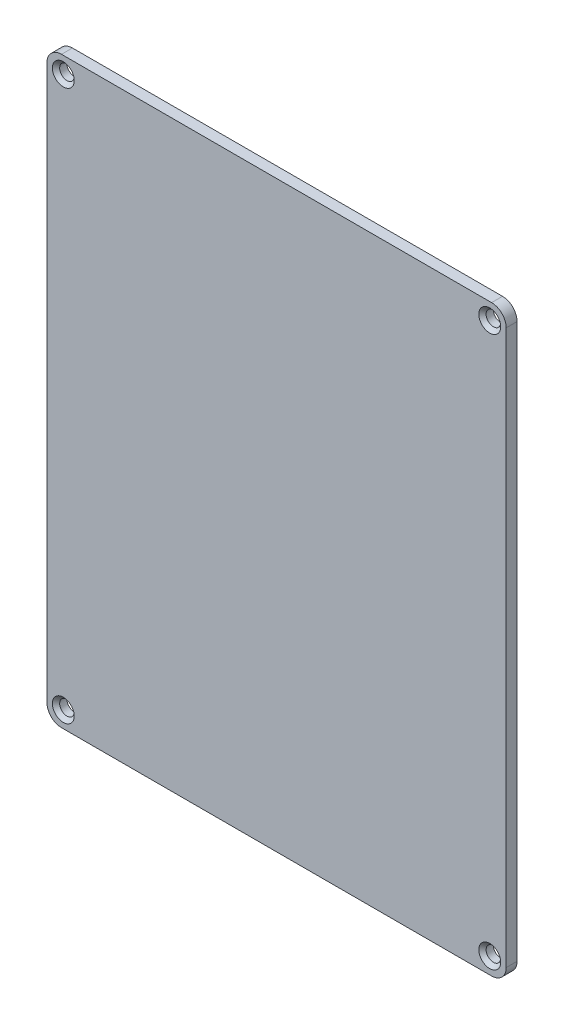
SolidWorks part; units mm, degrees
ref_plane "Ön Düzlem" through (0, 0, 0) normal (0, 0, 1) x (1, 0, 0)
ref_plane "Üst Düzlem" through (0, 0, 0) normal (0, 1, 0) x (1, 0, 0)
ref_plane "Sağ Düzlem" through (0, 0, 0) normal (1, 0, 0) x (0, 0, -1)
sketch "Çizim1" plane through (0, 0, 0) normal (0, 0, 1) x (1, 0, 0)
  line L1 (-31.5, -40) -> (31.5, -40)
  line L2 (-31.5, -40) -> (-31.5, 40)
  line L3 (-31.5, 40) -> (31.5, 40)
  line L4 (31.5, -40) -> (31.5, 40)
  line L5 (-31.5, -40) -> (31.5, 40) construction
  line L6 (-31.5, 40) -> (31.5, -40) construction
  point P0 (0, 0)
  dimension "D1" = 63
  dimension "D2" = 80
extrude "Yükseklik-Ekstrüzyon1" add sketch "Çizim1" along normal blind 1.5
sketch "Çizim2" plane through (0, 0, 1.5) normal (0, 0, 1) x (1, 0, 0)
  line L0 (-31.5, 40) -> (-31.5, -40) construction
  line L1 (31.5, 40) -> (-31.5, 40) construction
  line L2 (0, 50.6239) -> (0, -52.6269) construction
  line L3 (-61.3665, 0) -> (80.4297, 0) construction
  circle A0 centre (-29.25, 37.75) radius 1
  circle A1 centre (29.25, 37.75) radius 1
  circle A2 centre (29.25, -37.75) radius 1
  circle A3 centre (-29.25, -37.75) radius 1
  dimension "D1" = 2
  dimension "D2" = 2.25
  dimension "D3" = 2.25
extrude "Kes-Ekstrüzyon1" cut sketch "Çizim2" against normal blind 1.5
fillet "Radyus1" radius 2 4 edges at (-31.5, -40, 0.75) (31.5, -40, 0.75) (31.5, 40, 0.75) (-31.5, 40, 0.75)
chamfer "Pah1" distance 0.5 angle 45 4 edges at (-28.25, 37.75, 1.5) (28.25, 37.75, 1.5) (-30.25, -37.75, 1.5) (30.25, -37.75, 1.5)
